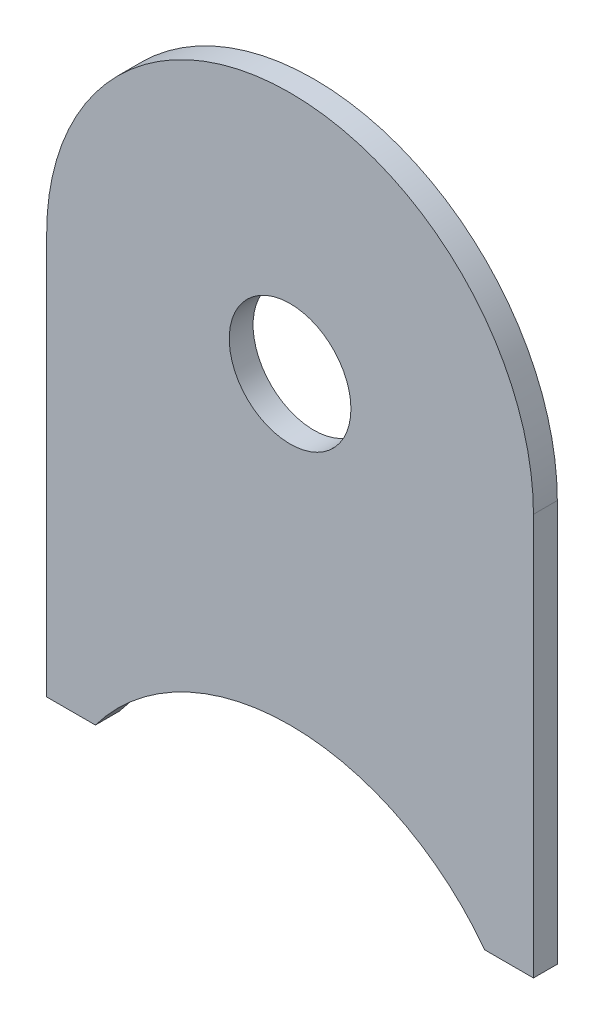
SolidWorks part; units mm, degrees
ref_plane "Front Plane" through (0, 0, 0) normal (0, 0, 1) x (1, 0, 0)
ref_plane "Top Plane" through (0, 0, 0) normal (0, 1, 0) x (1, 0, 0)
ref_plane "Right Plane" through (0, 0, 0) normal (1, 0, 0) x (0, 0, -1)
sketch "Sketch1" plane through (0, 0, 0) normal (0, 0, 1) x (1, 0, 0)
  line L0 (0, 0) -> (2.54, 0)
  line L2 (0, 0) -> (0, 20.955)
  line L4 (25.4, 0) -> (25.4, 20.955)
  line L5 (22.86, 0) -> (25.4, 0)
  circle A0 centre (12.7, 20.955) radius 3.175
  arc A2 (0, 20.955) -> (25.4, 20.955) centre (12.7, 20.955) cw
  arc A3 (22.86, 0) -> (2.54, 0) centre (12.7, -7.62) ccw
  point P2 (0, 0)
  point P7 (0, 0)
  dimension "D1" = 12.7
  dimension "D2" = 25.4
  dimension "D3" = 6.35
  dimension "D4" = 7.62
  dimension "D5" = 28.575
extrude "Boss-Extrude1" add sketch "Sketch1" along normal blind 1.2446
